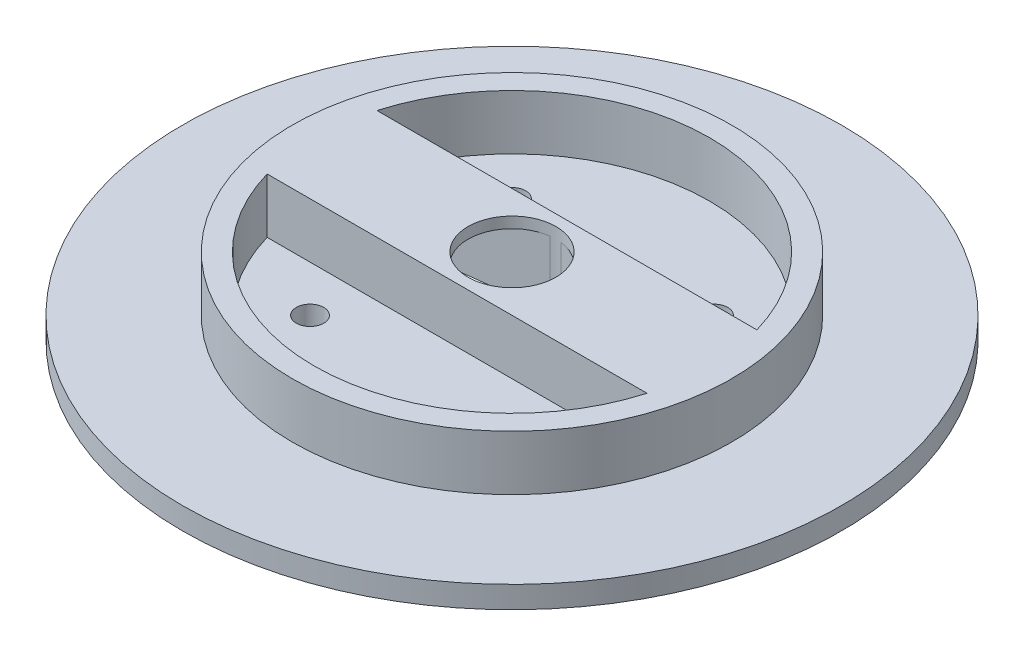
SolidWorks part; units mm, degrees
ref_plane "前视基准面" through (0, 0, 0) normal (0, 0, 1) x (1, 0, 0)
ref_plane "上视基准面" through (0, 0, 0) normal (0, 1, 0) x (1, 0, 0)
ref_plane "右视基准面" through (0, 0, 0) normal (1, 0, 0) x (0, 0, -1)
other "Configuration Table"
sketch "草图1" plane through (0, 0, 0) normal (0, 1, 0) x (1, 0, 0)
  line L0 (0, 0) -> (31.384, 31.384) construction
  line L1 (-35.2676, 0) -> (38.0577, 0) construction
  circle A0 centre (0, 0) radius 30
  circle A1 centre (9.1924, 9.1924) radius 1.25
  circle A2 centre (9.1924, -9.1924) radius 1.25
  circle A3 centre (-9.1924, -9.1924) radius 1.25
  circle A4 centre (-9.1924, 9.1924) radius 1.25
  point P17 (0, 0)
  dimension "D1" = 60
  dimension "D3" = 13
  dimension "D4" = 2.5
  dimension "D2" = 45
  dimension "D5" = 4
extrude "凸台-拉伸1" add sketch "草图1" along normal blind 2
sketch "草图2" plane through (0, 2, 0) normal (0, 1, 0) x (1, 0, 0)
  line L0 (-23.2378, 0) -> (23.2711, 0) construction
  line L1 (-17.2916, 5) -> (17.2916, 5)
  line L2 (-17.2916, -5) -> (17.2916, -5)
  circle A0 centre (0, 0) radius 20
  arc A1 (-17.2916, -5) -> (17.2916, -5) centre (0, 0) ccw
  circle A2 centre (0, 0) radius 18 construction
  arc A3 (17.2916, 5) -> (-17.2916, 5) centre (0, 0) ccw
  dimension "D1" = 40
  dimension "D3" = 10
  dimension "D2" = 2
extrude "凸台-拉伸2" add sketch "草图2" along normal blind 5
sketch "草图4" plane through (0, 0, 0) normal (0, -1, 0) x (-1, 0, 0)
  line L0 (16.4354, 0) -> (-16.2719, 0) construction
  line L1 (0, -8.6957) -> (0, 8.9481) construction
  line L2 (-0.5, -3.9686) -> (-16.25, -1.9843)
  line L3 (-0.5, 3.9686) -> (-16.25, 1.9843)
  line L4 (0.5, 3.9686) -> (16.25, 1.9843)
  line L5 (0.5, -3.9686) -> (16.25, -1.9843)
  arc A0 (-0.5, -3.9686) -> (0.5, -3.9686) centre (0, 0) ccw
  arc A1 (-16.25, 1.9843) -> (-16.25, -1.9843) centre (-16, 0) ccw
  arc A2 (16.25, 1.9843) -> (16.25, -1.9843) centre (16, 0) cw
  arc A3 (0.5, 3.9686) -> (-0.5, 3.9686) centre (0, 0) ccw
  dimension "D1" = 8
  dimension "D2" = 4
  dimension "D3" = 32
extrude "切除-拉伸1" cut sketch "草图4" against normal blind 6
sketch "草图5" plane through (0, 6, 0) normal (0, -1, 0) x (-1, 0, 0)
  circle A0 centre (0, 0) radius 4
extrude "切除-拉伸2" cut sketch "草图5" against normal blind 6
